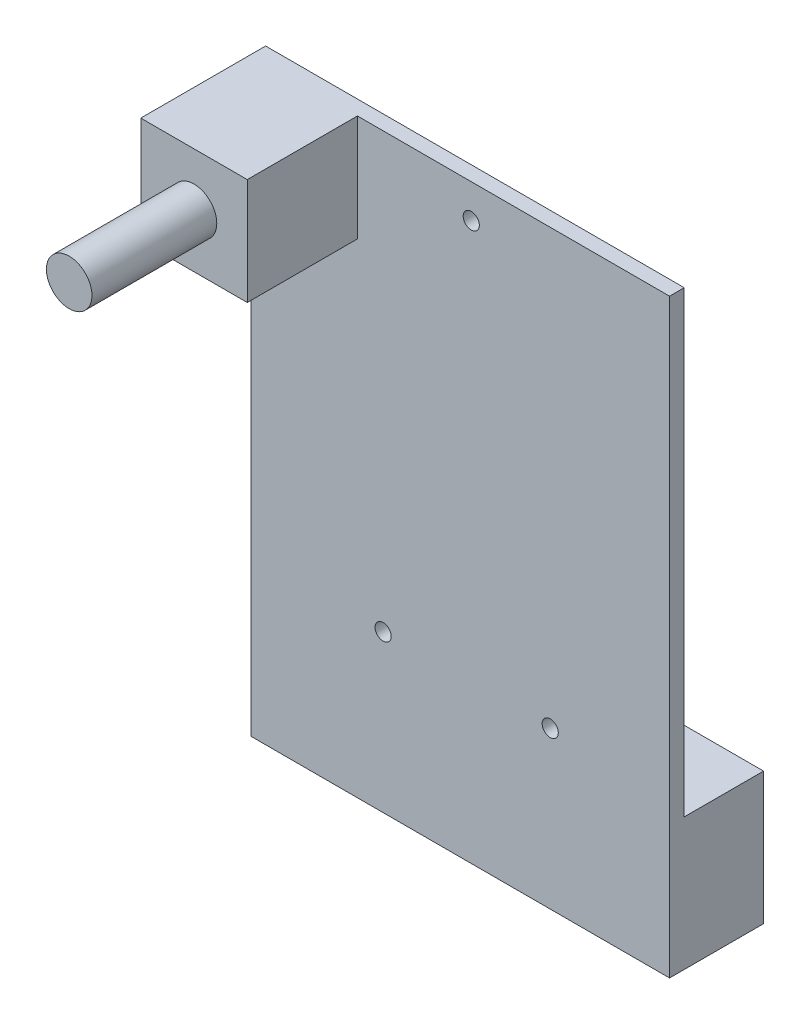
SolidWorks part; units mm, degrees
ref_plane "Front Plane" through (0, 0, 0) normal (1, 0, 0) x (0, 1, 0)
ref_plane "Top Plane" through (0, 0, 0) normal (0, 0, 1) x (0, 1, 0)
ref_plane "Right Plane" through (0, 0, 0) normal (0, 1, 0) x (-1, 0, 0)
sketch "Sketch1" plane through (0, 0, 0) normal (0, 0, 1) x (0, 1, 0)
  line L0 (0, 28.5) -> (0, -28.5) construction
  line L1 (-40.2, 28.5) -> (40.2, 28.5)
  line L2 (-40.2, 28.5) -> (-40.2, -28.5)
  line L3 (-40.2, -28.5) -> (40.2, -28.5)
  line L4 (40.2, 28.5) -> (40.2, -28.5)
  line L5 (-40.2, 0) -> (40.2, 0) construction
  point P8 (0, 0)
  dimension "D1" = 80.4
  dimension "D2" = 57
extrude "Boss-Extrude1" add sketch "Sketch1" along normal blind 17
sketch "Sketch2" plane through (0, 0, 17) normal (0, 0, 1) x (1, 0, 0)
  line L0 (-28.5, 25.7) -> (-14, 40.2) construction
  line L1 (-28.5, 40.2) -> (-14, 40.2)
  line L2 (-28.5, 40.2) -> (-28.5, 25.7)
  line L3 (-28.5, 25.7) -> (-14, 25.7)
  line L4 (-14, 40.2) -> (-14, 25.7)
  line L5 (-28.5, 40.2) -> (-14, 25.7) construction
  circle A0 centre (-21.25, 32.95) radius 3.1
  dimension "D3" = 6.2
  dimension "D1" = 14.5
  dimension "D2" = 14.5
extrude "Boss-Extrude2" add sketch "Sketch2" along normal blind 17 contours A0
sketch "Sketch3" plane through (0, 0, 0) normal (0, 0, -1) x (1, 0, 0)
  line L0 (28.5, 40.2) -> (28.5, -40.2) construction
  line L1 (-28.5, 40.2) -> (28.5, 40.2)
  line L2 (-28.5, 40.2) -> (-28.5, 22.2)
  line L3 (-28.5, 22.2) -> (28.5, 22.2)
  line L4 (28.5, 40.2) -> (28.5, 22.2)
  dimension "D1" = 18
extrude "Boss-Extrude3" add sketch "Sketch3" along normal offset from surface (10.8 mm away) 27.8 up to face at (-18.15, 32.95, 17)
sketch "Sketch4" plane through (0, 0, 17) normal (0, 0, 1) x (1, 0, 0)
  line L0 (-14, 40.2) -> (-14, 25.7)
  line L1 (-14, 25.7) -> (-28.5, 25.7)
  line L2 (-28.5, 25.7) -> (-28.5, -40.2)
  line L3 (-28.5, -40.2) -> (28.5, -40.2)
  line L4 (28.5, -40.2) -> (28.5, 40.2)
  line L5 (28.5, 40.2) -> (-14, 40.2)
extrude "Cut-Extrude1" cut sketch "Sketch4" against normal blind 15
sketch "Sketch5" plane through (0, 0, 0) normal (0, 0, -1) x (1, 0, 0)
  line L0 (-28.5, -40.2) -> (-28.5, 22.2) construction
  line L2 (-28.5, 40.2) -> (28.5, 40.2) construction
  line L3 (28.5, -40.2) -> (-28.5, -40.2) construction
  line L5 (-28.5, -40.2) -> (-28.5, -25.7) construction
  circle A0 centre (1.5, -35.6) radius 1.1
  circle A1 centre (-10.5, 18.8773) radius 1.1
  circle A2 centre (12.25, 18.8715) radius 1.1
  dimension "D1" = 22.75
  dimension "D6" = 2.2
  dimension "D7" = 2.2
  dimension "D10" = 2.2
  dimension "D2" = 18
  dimension "D3" = 21.3227
  dimension "D4" = 21.3285
  dimension "D5" = 18
  dimension "D8" = 4.6
  dimension "D9" = 30
extrude "Cut-Extrude2" cut sketch "Sketch5" against normal through all both and the other way through all
sketch "Sketch6" plane through (0, 0, 2) normal (0, 0, 1) x (1, 0, 0)
sketch "Sketch7" plane through (0, 0, 2) normal (0, 0, 1) x (1, 0, 0)
  line L0 (23.1, 27.85) -> (23.1, 20.35) construction
  line L1 (26.7, 27.85) -> (26.7, 20.35)
  line L2 (19.5, 27.85) -> (19.5, 20.35)
  line L3 (23.1, -5.55) -> (23.1, -13.05) construction
  line L4 (26.7, -5.55) -> (26.7, -13.05)
  line L5 (19.5, -5.55) -> (19.5, -13.05)
  line L6 (23.1, 11.15) -> (23.1, 3.65) construction
  line L7 (-14, 40.2) -> (-14, 25.7) construction
  line L8 (28.5, 40.2) -> (-14, 40.2) construction
  line L9 (26.7, 11.15) -> (26.7, 3.65)
  line L10 (19.5, 11.15) -> (19.5, 3.65)
  line L11 (23.1, 16.75) -> (23.1, 14.75)
  line L12 (23.1, 0.05) -> (23.1, -1.95)
  line L13 (28.5, -40.2) -> (28.5, 40.2) construction
  arc A0 (26.7, 27.85) -> (19.5, 27.85) centre (23.1, 27.85) ccw
  arc A1 (19.5, 20.35) -> (26.7, 20.35) centre (23.1, 20.35) ccw
  arc A2 (26.7, -5.55) -> (19.5, -5.55) centre (23.1, -5.55) ccw
  arc A3 (19.5, -13.05) -> (26.7, -13.05) centre (23.1, -13.05) ccw
  arc A4 (26.7, 11.15) -> (19.5, 11.15) centre (23.1, 11.15) ccw
  arc A5 (19.5, 3.65) -> (26.7, 3.65) centre (23.1, 3.65) ccw
  point P2 (23.1, 24.1)
  point P7 (23.1, -9.3)
  point P16 (23.1, 7.4)
  point P31 (23.1, 31.45)
  dimension "D5" = 3.6
  dimension "D6" = 3.6
  dimension "D7" = 3.6
  dimension "D3" = 3.6
  dimension "D1" = 7.5
  dimension "D2" = 7.5
  dimension "D4" = 7.5
  dimension "D8" = 1.8
  dimension "D9" = 2
  dimension "D10" = 8.75
